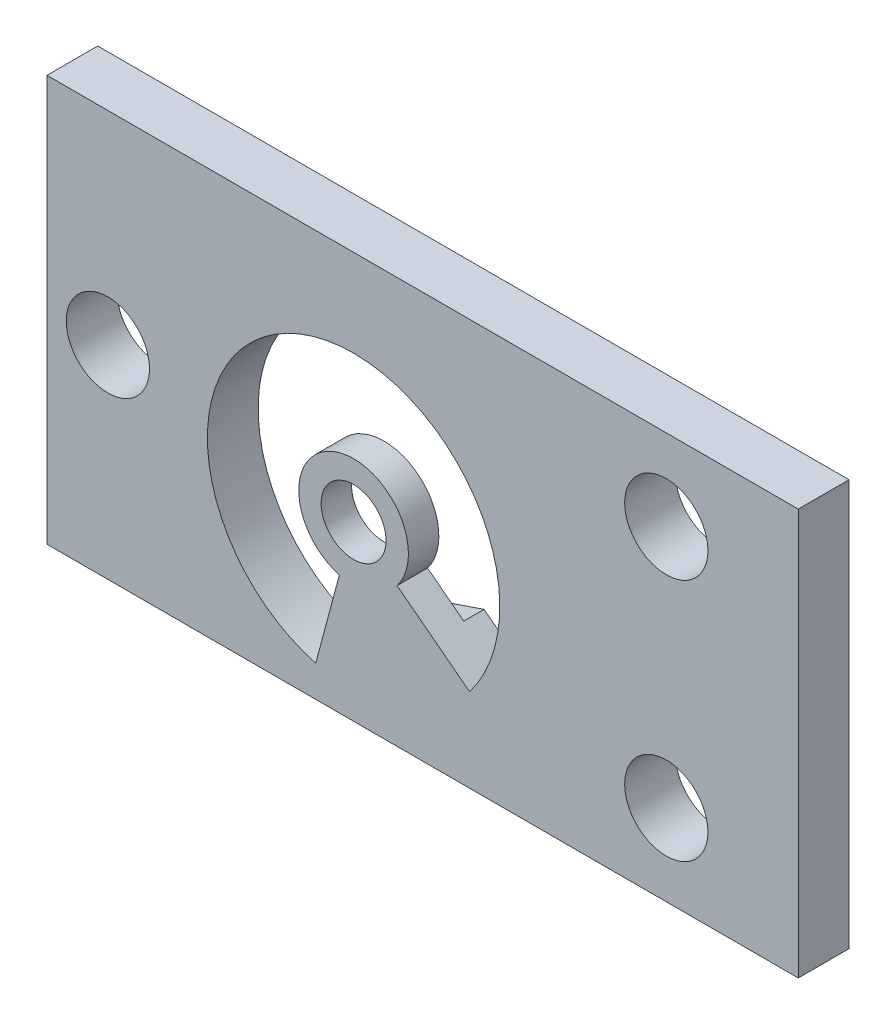
SolidWorks part; units mm, degrees
ref_plane "Plan de face" through (0, 0, 0) normal (0, 0, 1) x (1, 0, 0)
ref_plane "Plan de dessus" through (0, 0, 0) normal (0, 1, 0) x (1, 0, 0)
ref_plane "Plan de droite" through (0, 0, 0) normal (1, 0, 0) x (0, 0, -1)
sketch "Esquisse1" plane through (0, 0, 0) normal (0, 0, 1) x (1, 0, 0)
  line L0 (-12, 6) -> (-12, -6) construction
  line L1 (18.5, -10) -> (-18.5, -10)
  line L2 (18.5, -10) -> (18.5, 10)
  line L3 (18.5, 10) -> (-18.5, 10)
  line L4 (-18.5, -10) -> (-18.5, 10)
  line L5 (18.5, -10) -> (-18.5, 10) construction
  line L6 (18.5, 10) -> (-18.5, -10) construction
  line L7 (-2.312, -5.8833) -> (1.258, -3.1437)
  line L8 (4.0988, -4.108) -> (5.2635, -8.4547)
  line L9 (3.4, -1.5) -> (3.4, -14.822) construction
  circle A0 centre (-12, 6) radius 2.05
  circle A1 centre (-12, -6) radius 2.05
  circle A2 centre (15.5, 0) radius 2.05
  circle A3 centre (3.4, -1.5) radius 8 construction
  arc A4 (5.2635, -8.4547) -> (-2.312, -5.8833) centre (3.4, -1.5) ccw construction
  arc A5 (4.0988, -4.108) -> (1.258, -3.1437) centre (3.4, -1.5) ccw
  arc A6 (-2.312, -5.8833) -> (5.2635, -8.4547) centre (3.4, -1.5) cw
  circle A7 centre (3.4, -1.5) radius 1.6
  point P0 (0, 0)
  point P13 (-12, 0)
  dimension "D3" = 4.1
  dimension "D8" = 16
  dimension "D9" = 11.5
  dimension "D10" = 15.1
  dimension "D12" = 0.8
  dimension "D14" = 3.2
  dimension "D1" = 37
  dimension "D2" = 20
  dimension "D4" = 12
  dimension "D5" = 27.5
  dimension "D6" = 4
  dimension "D7" = 6.5
  dimension "D13" = 3
  dimension "D15" = 15
  dimension "D11" = 4.5
extrude "Boss.-Extru.1" add sketch "Esquisse1" along normal blind 2.5 contours L4 L1 L2 L3 A2 A1 A0 L7 A6 L8 A5
sketch "Esquisse3" plane through (0, 0, 0) normal (0, 0, -1) x (-1, 0, 0)
  line L0 (2.312, -5.8833) -> (-1.258, -3.1437) construction
  line L1 (-4.0988, -4.108) -> (-5.2635, -8.4547) construction
  line L2 (2.312, -5.8833) -> (0.527, -4.5135)
  line L3 (-4.6812, -6.2813) -> (-5.2635, -8.4547)
  line L4 (18.5, -10) -> (18.5, 10)
  line L5 (18.5, 10) -> (-18.5, 10)
  line L6 (-18.5, 10) -> (-18.5, -10)
  line L7 (-18.5, -10) -> (18.5, -10)
  line L8 (18.5, -10) -> (18.5, 10)
  line L9 (18.5, 10) -> (-18.5, 10)
  line L10 (-18.5, 10) -> (-18.5, -10)
  line L11 (-18.5, -10) -> (18.5, -10)
  line L12 (-4.6812, -6.2813) -> (0.527, -4.5135)
  arc A2 (2.312, -5.8833) -> (-5.2635, -8.4547) centre (-3.4, -1.5) ccw construction
  arc A3 (2.312, -5.8833) -> (-5.2635, -8.4547) centre (-3.4, -1.5) ccw
  dimension "D1" = 0
extrude "Enlèv. mat.-Extru.1" cut sketch "Esquisse3" against normal blind 1
ref_plane "Plan1" through (18.5, 0, 0) normal (1, 0, 0) x (0, 0, -1)
mirror "Symétrie1" about plane through (18.5, 0, 0) normal (1, 0, 0) of "Enlèv. mat.-Extru.1", "Boss.-Extru.1"
sketch "Esquisse5" plane through (18.5, 0, 0) normal (1, 0, 0) x (0, 0, -1)
  line L4 (0, -10) -> (0, 10)
  line L5 (0, 10) -> (-2.5, 10)
  line L6 (-2.5, 10) -> (-2.5, -10)
  line L7 (-2.5, -10) -> (0, -10)
  line L8 (0, -10) -> (0, 10)
  line L9 (0, 10) -> (-2.5, 10)
  line L10 (-2.5, 10) -> (-2.5, -10)
  line L11 (-2.5, -10) -> (0, -10)
  dimension "D1" = 0
extrude "Enlèv. mat.-Extru.3" cut sketch "Esquisse5" against normal through all
